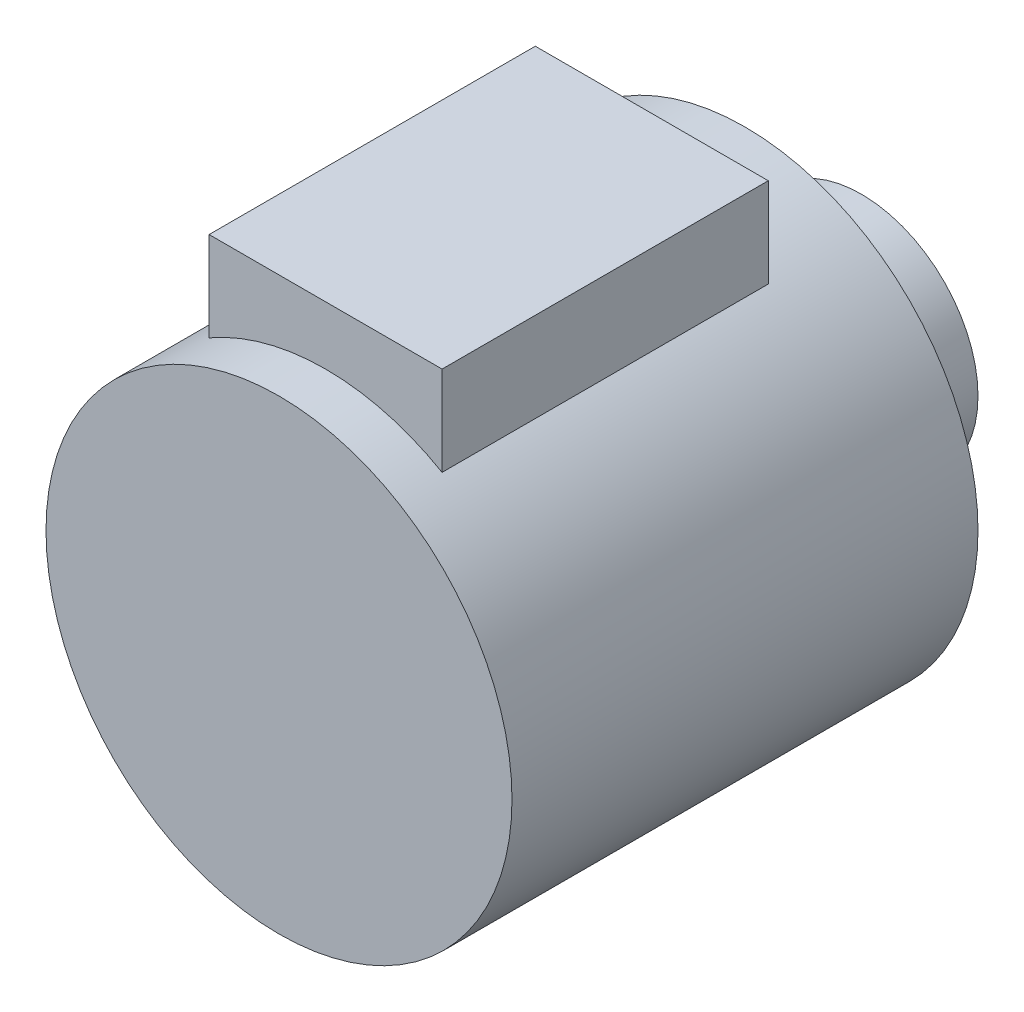
SolidWorks part; units mm, degrees
ref_plane "前视基准面" through (0, 0, 0) normal (0, 0, 1) x (1, 0, 0)
ref_plane "上视基准面" through (0, 0, 0) normal (0, 1, 0) x (1, 0, 0)
ref_plane "右视基准面" through (0, 0, 0) normal (1, 0, 0) x (0, 0, -1)
sketch "草图1" plane through (0, 0, 0) normal (0, 0, 1) x (1, 0, 0)
  circle A0 centre (0, 0) radius 10
extrude "凸台-拉伸1" add sketch "草图1" along normal blind 10
sketch "草图2" plane through (0, 0, 10) normal (0, 0, 1) x (1, 0, 0)
  circle A0 centre (0, 0) radius 20
extrude "凸台-拉伸2" add sketch "草图2" along normal blind 40
sketch "草图3" plane through (0, 0, 0) normal (0, 1, 0) x (1, 0, 0)
  line L0 (10, -18) -> (10, -46)
  line L3 (-10, -18) -> (-10, -46)
  line L6 (-10, -18) -> (10, -18)
  line L7 (-10, -46) -> (10, -46)
extrude "凸台-拉伸3" add sketch "草图3" along normal blind 25
